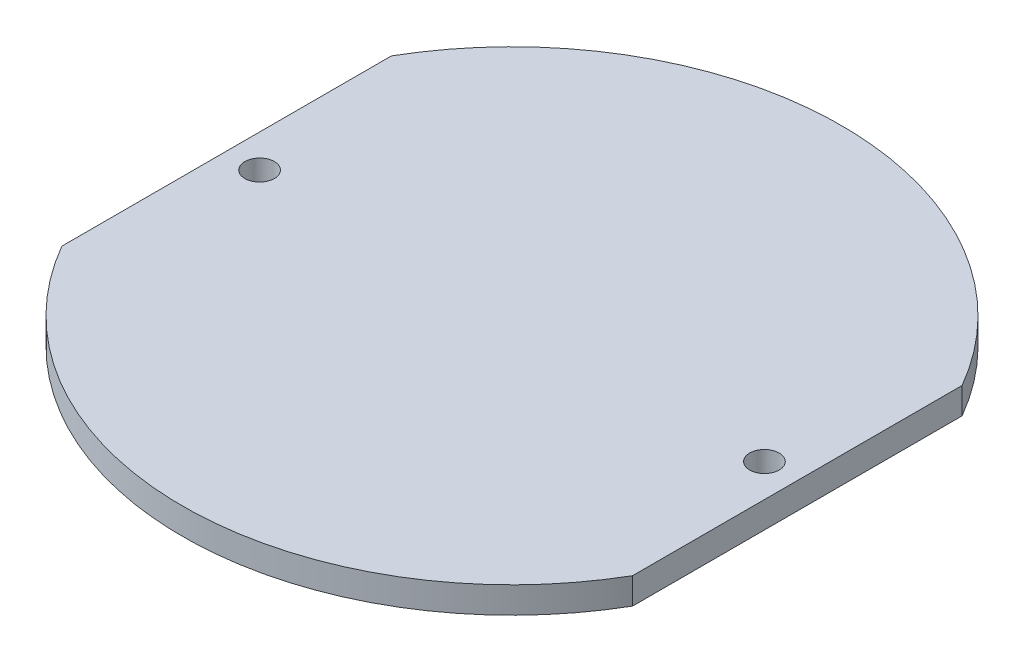
SolidWorks part; units mm, degrees
ref_plane "Front Plane" through (0, 0, 0) normal (0, 0, 1) x (1, 0, 0)
ref_plane "Top Plane" through (0, 0, 0) normal (0, 1, 0) x (1, 0, 0)
ref_plane "Right Plane" through (0, 0, 0) normal (1, 0, 0) x (0, 0, -1)
sketch "Sketch1" plane through (0, 0, 0) normal (0, 1, 0) x (1, 0, 0)
  line L0 (-27.4963, 15.875) -> (-27.4963, -15.875)
  line L1 (27.4963, 15.875) -> (27.4963, -15.875)
  line L2 (0, 31.75) -> (0, -31.75) construction
  line L3 (-27.4963, 0) -> (27.4963, 0) construction
  arc A0 (-27.4963, -15.875) -> (27.4963, -15.875) centre (0, 0) ccw
  arc A1 (27.4963, 15.875) -> (-27.4963, 15.875) centre (0, 0) ccw
  circle A2 centre (-24.3213, 0) radius 1.4224
  circle A3 centre (24.3213, 0) radius 1.4224
  dimension "D1" = 63.5
  dimension "D3" = 2.8448
  dimension "D2" = 60
  dimension "D4" = 3.175
extrude "Base" add sketch "Sketch1" along normal blind 2.54
